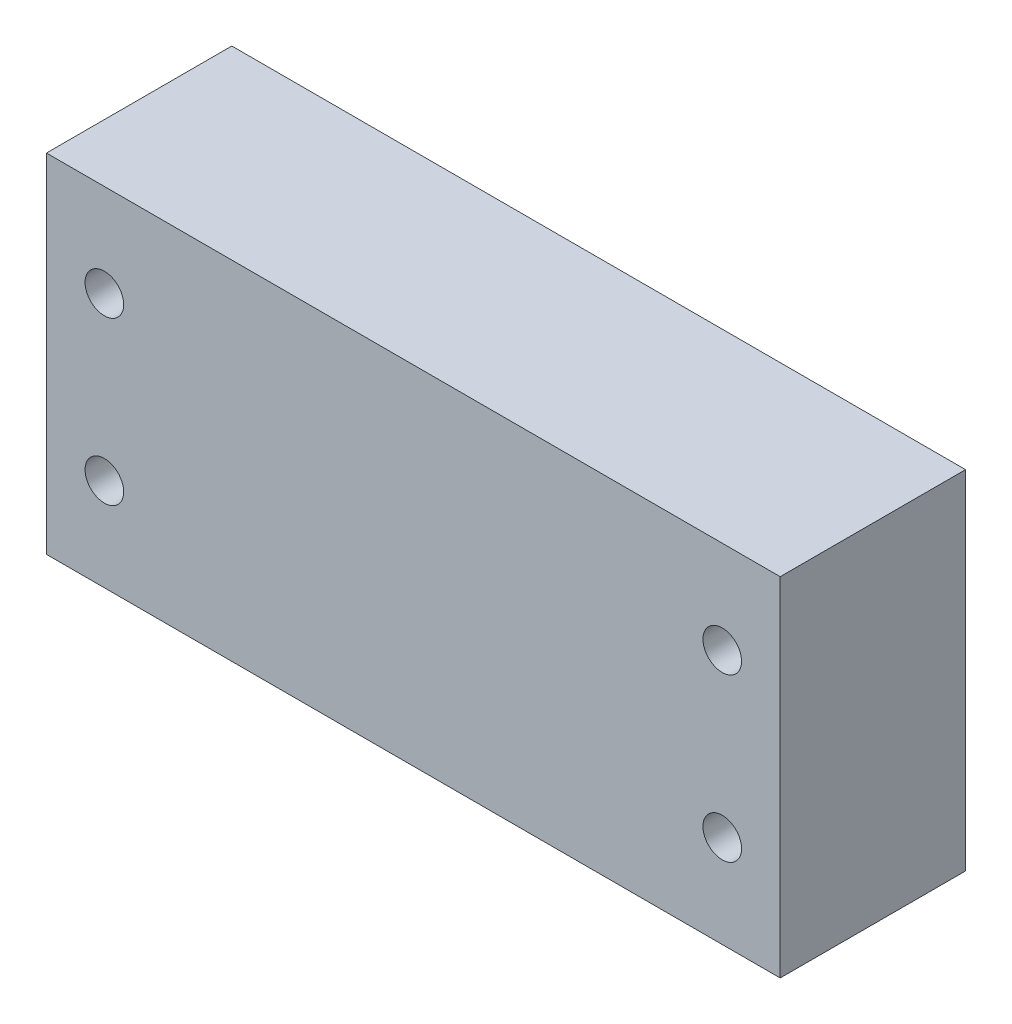
SolidWorks part; units mm, degrees
ref_plane "Front" through (0, 0, 0) normal (0, 0, 1) x (1, 0, 0)
ref_plane "Top" through (0, 0, 0) normal (0, 1, 0) x (1, 0, 0)
ref_plane "Right" through (0, 0, 0) normal (1, 0, 0) x (0, 0, -1)
sketch "Sketch1" plane through (0, 0, 0) normal (0, 0, 1) x (1, 0, 0)
  line L1 (-47.5, 22.5) -> (47.5, 22.5)
  line L2 (-47.5, 22.5) -> (-47.5, -22.5)
  line L3 (-47.5, -22.5) -> (47.5, -22.5)
  line L4 (47.5, 22.5) -> (47.5, -22.5)
  line L5 (-47.5, 22.5) -> (47.5, -22.5) construction
  line L6 (-47.5, -22.5) -> (47.5, 22.5) construction
  point P0 (0, 0)
  dimension "D1" = 95
  dimension "D2" = 45
extrude "Boss-Extrude1" add sketch "Sketch1" along normal blind 24
sketch "Sketch2" plane through (0, 0, 24) normal (0, 0, 1) x (1, 0, 0)
  line L1 (-40, -10.5) -> (40, -10.5) construction
  line L2 (-40, -10.5) -> (-40, 10.5) construction
  line L3 (-40, 10.5) -> (40, 10.5) construction
  line L4 (40, -10.5) -> (40, 10.5) construction
  line L5 (-40, -10.5) -> (40, 10.5) construction
  line L6 (-40, 10.5) -> (40, -10.5) construction
  circle A0 centre (-40, 10.5) radius 2.5
  circle A1 centre (-40, -10.5) radius 2.5
  circle A2 centre (40, -10.5) radius 2.5
  circle A3 centre (40, 10.5) radius 2.5
  point P0 (0, 0)
  dimension "D3" = 5
  dimension "D1" = 21
  dimension "D2" = 80
extrude "Cut-Extrude1" cut sketch "Sketch2" against normal through all
